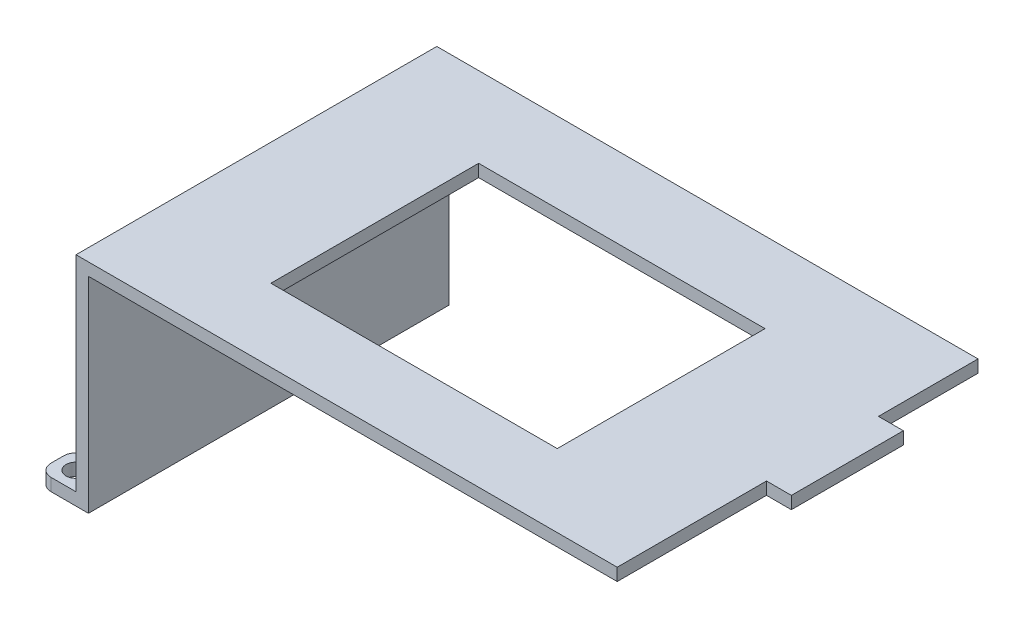
SolidWorks part; units mm, degrees
ref_plane "前视基准面" through (0, 0, 0) normal (0, 0, 1) x (1, 0, 0)
ref_plane "上视基准面" through (0, 0, 0) normal (0, 1, 0) x (1, 0, 0)
ref_plane "右视基准面" through (0, 0, 0) normal (1, 0, 0) x (0, 0, -1)
other "Configuration Table"
sketch "草图1" plane through (0, 0, 0) normal (0, 1, 0) x (1, 0, 0)
  line L1 (43.5, -29) -> (-43.5, -29)
  line L2 (43.5, -29) -> (43.5, 29)
  line L3 (43.5, 29) -> (-43.5, 29)
  line L4 (-43.5, -29) -> (-43.5, 29)
  line L5 (43.5, -29) -> (-43.5, 29) construction
  line L6 (43.5, 29) -> (-43.5, -29) construction
  line L7 (43.5, 13) -> (47.5, 13)
  line L8 (43.5, 13) -> (43.5, -5)
  line L9 (43.5, -5) -> (47.5, -5)
  line L10 (47.5, 13) -> (47.5, -5)
  point P0 (0, 0)
  dimension "D1" = 58
  dimension "D2" = 87
  dimension "D3" = 4
  dimension "D4" = 16
  dimension "D5" = 18
extrude "凸台-拉伸1" add sketch "草图1" along normal blind 2 contours L4 L1 L2 L3 | L10 L7 L2 L9
sketch "草图2" plane through (0, 0, 0) normal (0, -1, 0) x (1, 0, 0)
  line L1 (-43.5, 29) -> (-41.5, 29)
  line L2 (-43.5, 29) -> (-43.5, -29)
  line L3 (-43.5, -29) -> (-41.5, -29)
  line L4 (-41.5, 29) -> (-41.5, -29)
  line L8 (-43.5, 29) -> (-43.5, -29)
  line L9 (-43.5, -29) -> (43.5, -29)
  line L10 (43.5, -29) -> (43.5, -13)
  line L11 (43.5, -13) -> (47.5, -13)
  line L12 (47.5, -13) -> (47.5, 5)
  line L13 (47.5, 5) -> (43.5, 5)
  line L14 (43.5, 5) -> (43.5, 29)
  line L15 (43.5, 29) -> (-43.5, 29)
  line L16 (-43.5, 29) -> (-43.5, -29)
  line L17 (-43.5, -29) -> (43.5, -29)
  line L18 (43.5, -29) -> (43.5, -13)
  line L19 (43.5, -13) -> (47.5, -13)
  line L20 (47.5, -13) -> (47.5, 5)
  line L21 (47.5, 5) -> (43.5, 5)
  line L22 (43.5, 5) -> (43.5, 29)
  line L23 (43.5, 29) -> (-43.5, 29)
  line M11 (-43.5, 29) -> (-43.5, -29)
  line M12 (-43.5, -29) -> (43.5, -29)
  line M18 (43.5, 29) -> (-43.5, 29)
  dimension "D2" = 2
  dimension "D1" = 0
extrude "凸台-拉伸2" add sketch "草图2" along normal blind 33 contours L4 M18 M11 M12
sketch "草图3" plane through (0, -33, 0) normal (0, -1, 0) x (1, 0, 0)
  line L0 (-46.5, 29) -> (-46.5, 23) construction
  line L1 (-43.5, 29) -> (-47.5, 29)
  line L2 (-43.5, 29) -> (-43.5, 23)
  line L3 (-43.5, 23) -> (-47.5, 23)
  line L4 (-41.5, -29) -> (-41.5, 29)
  line L5 (-41.5, 29) -> (-43.5, 29)
  line L6 (-43.5, 29) -> (-43.5, -29)
  line L7 (-43.5, -29) -> (-41.5, -29)
  line L8 (-41.5, -29) -> (-41.5, 29)
  line L9 (-41.5, 29) -> (-43.5, 29)
  line L10 (-43.5, 29) -> (-43.5, -29)
  line L11 (-43.5, -29) -> (-41.5, -29)
  line L12 (-49.5, 27) -> (-49.5, 25)
  line L13 (-43.5, -29) -> (-47.5, -29)
  line L14 (-43.5, -29) -> (-43.5, -23)
  line L15 (-43.5, -23) -> (-47.5, -23)
  line L16 (-49.5, -27) -> (-49.5, -25)
  line L17 (-49.5, 26) -> (-43.5, 26) construction
  line L18 (-46.5, -23) -> (-46.5, -29) construction
  line L19 (-49.5, -26) -> (-43.5, -26) construction
  circle A0 centre (-46.5, 26) radius 1.6
  circle A1 centre (-46.5, -26) radius 1.6
  arc A2 (-47.5, 23) -> (-49.5, 25) centre (-47.5, 25) cw
  arc A3 (-47.5, 29) -> (-49.5, 27) centre (-47.5, 27) ccw
  arc A4 (-47.5, -29) -> (-49.5, -27) centre (-47.5, -27) cw
  arc A5 (-47.5, -23) -> (-49.5, -25) centre (-47.5, -25) ccw
  point P24 (-49.5, 23)
  point P27 (-49.5, 29)
  point P30 (-49.5, -29)
  point P33 (-49.5, -23)
  line M11 (-43.5, 29) -> (-43.5, -29)
  dimension "D6" = 3.2
  dimension "D7" = 3.2
  dimension "D8" = 2
  dimension "D2" = 6
  dimension "D3" = 6
  dimension "D4" = 6
  dimension "D5" = 6
  dimension "D9" = 3
  dimension "D10" = 3
  dimension "D11" = 52
  dimension "D1" = 0
extrude "凸台-拉伸3" add sketch "草图3" against normal blind 2 contours L1 L12 L3 M11 | L16 L13 L10 L15
sketch "草图4" plane through (0, 2, 0) normal (0, 1, 0) x (1, 0, 0)
  line L1 (-23.8692, -17.3036) -> (22.169, -17.3036)
  line L2 (-23.8692, -17.3036) -> (-23.8692, 16.0934)
  line L3 (-23.8692, 16.0934) -> (22.169, 16.0934)
  line L4 (22.169, -17.3036) -> (22.169, 16.0934)
  point P4 (-18.9001, -12.9003)
extrude "切除-拉伸1" cut sketch "草图4" against normal up to next
